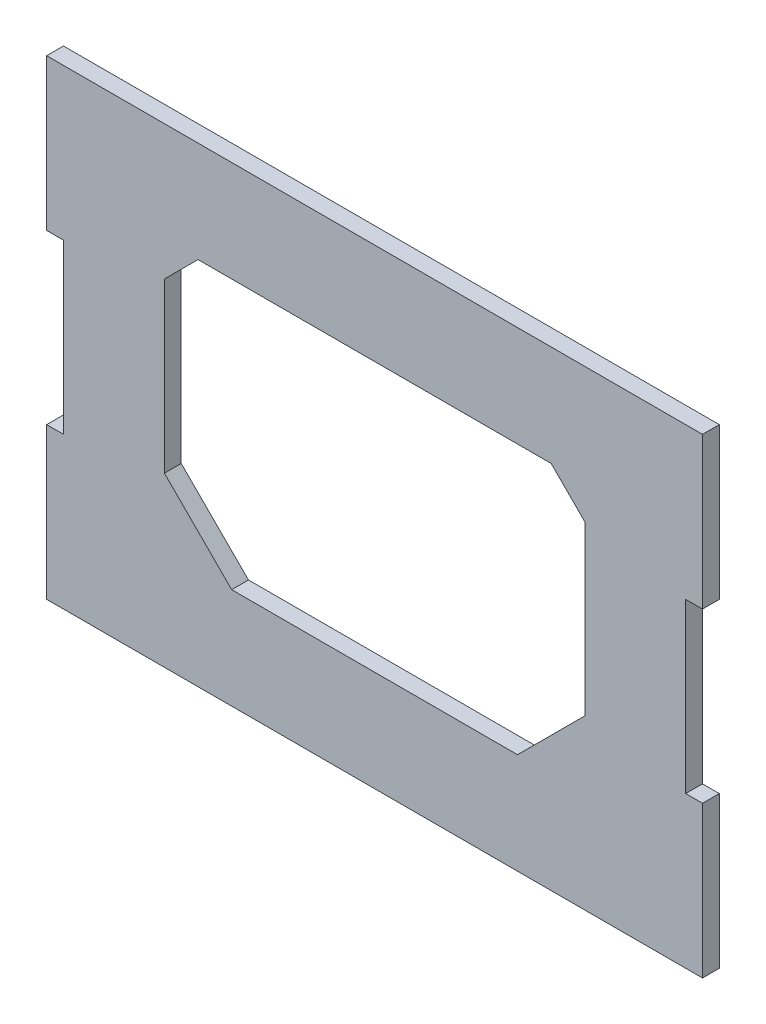
SolidWorks part; units mm, degrees
ref_plane "Plan de face" through (0, 0, 0) normal (0, 0, 1) x (1, 0, 0)
ref_plane "Plan de dessus" through (0, 0, 0) normal (0, 1, 0) x (1, 0, 0)
ref_plane "Plan de droite" through (0, 0, 0) normal (1, 0, 0) x (0, 0, -1)
sketch "Esquisse1" plane through (0, 0, 0) normal (0, 0, 1) x (1, 0, 0)
  line L0 (390, 140) -> (0, 140) construction
  line L1 (0, 0) -> (390, 0)
  line L2 (0, 0) -> (0, 280) construction
  line L3 (0, 280) -> (390, 280)
  line L4 (390, 0) -> (390, 280) construction
  line L5 (390, 0) -> (390, 90)
  line L6 (390, 90) -> (380, 90)
  line L7 (380, 90) -> (380, 190)
  line L8 (195, 140) -> (195, 0) construction
  line L9 (390, 190) -> (380, 190)
  line L10 (390, 280) -> (390, 190)
  line L11 (0, 280) -> (0, 190)
  line L12 (0, 190) -> (10, 190)
  line L13 (10, 90) -> (10, 190)
  line L14 (0, 90) -> (10, 90)
  line L15 (0, 0) -> (0, 90)
  point P13 (380, 140)
  dimension "D1" = 50
  dimension "D2" = 90
  dimension "D3" = 390
  dimension "D4" = 10
extrude "Boss.-Extru.2" add sketch "Esquisse1" along normal blind 10
sketch "Esquisse3" plane through (0, 0, 10) normal (0, 0, 1) x (1, 0, 0)
  line L0 (70, 100) -> (110, 60)
  line L1 (280, 60) -> (320, 100)
  line L2 (90, 220) -> (70, 200)
  line L3 (320, 200) -> (300, 220)
  line L24 (70, 60) -> (320, 60)
  line L25 (320, 60) -> (320, 220)
  line L26 (320, 220) -> (70, 220)
  line L27 (70, 220) -> (70, 60)
  line L28 (110, 60) -> (280, 60)
  line L29 (320, 100) -> (320, 200)
  line L30 (300, 220) -> (90, 220)
  line L31 (70, 200) -> (70, 100)
  point P1 (70, 220)
  point P4 (70, 60)
  point P6 (320, 60)
  point P8 (320, 220)
  dimension "D1" = 60
extrude "Enlèv. mat.-Extru.1" cut sketch "Esquisse3" against normal blind 10
